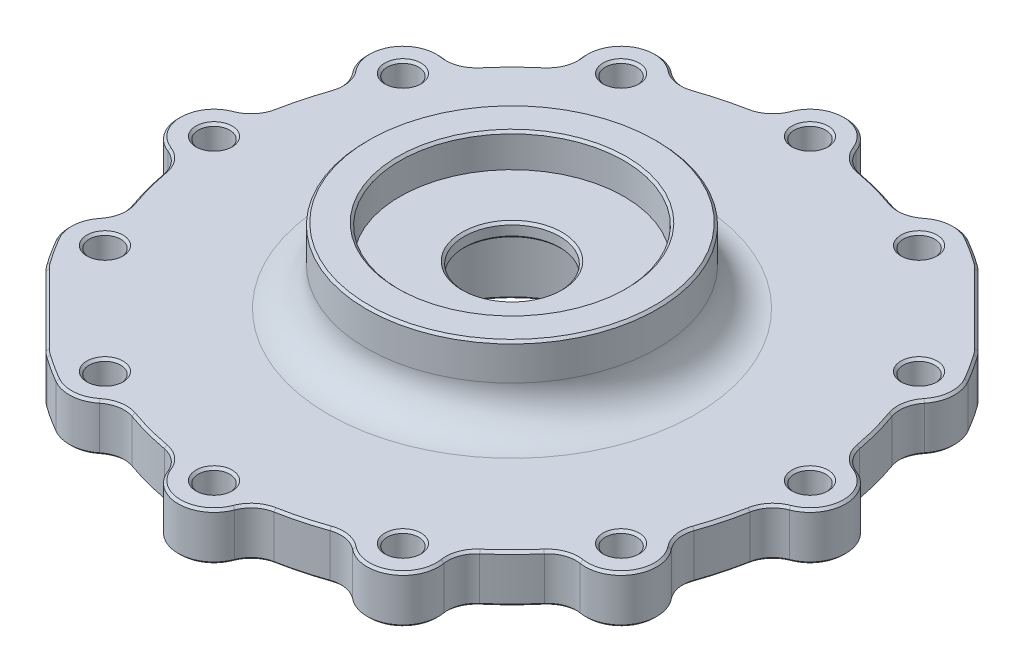
SolidWorks part; units mm, degrees
material "6061-T6 (SS)"
ref_plane "Front Plane" through (0, 0, 0) normal (0, 0, 1) x (1, 0, 0)
ref_plane "Top Plane" through (0, 0, 0) normal (0, 1, 0) x (1, 0, 0)
ref_plane "Right Plane" through (0, 0, 0) normal (1, 0, 0) x (0, 0, -1)
sketch "Sketch1" plane through (0, 0, 0) normal (0, 0, 1) x (1, 0, 0)
  line L1 (-70, -26.6983) -> (-45, -26.6983)
  line L18 (-45, -26.6983) -> (-45, -31.6983)
  line L23 (0, 95.7864) -> (0, -110.3116) construction
  line L28 (-70, -26.6983) -> (-70, -16.6983)
  line L29 (-70, -16.6983) -> (-38.5, -16.6983)
  line L30 (-30.5, -8.6983) -> (-30.5, -1.0983)
  line L31 (-30.5, -1.0983) -> (-23.5, -1.0983)
  line L32 (-23.5, -1.0983) -> (-23.5, -8.0983)
  line L40 (-23.5, -11.0983) -> (-10, -11.0983)
  line L41 (-10, -11.0983) -> (-10, -8.0983)
  line L42 (-10, -8.0983) -> (-23.5, -8.0983)
  line L43 (-23.5, -11.0983) -> (-23.5, -31.6983)
  line L44 (-45, -31.6983) -> (-23.5, -31.6983)
  line L45 (-38.5, -16.6983) -> (-70, -16.6983)
  arc A1 (-30.5, -8.6983) -> (-38.5, -16.6983) centre (-38.5, -8.6983) cw
  point P31 (-70, -16.6983)
  dimension "D1" = 45
  dimension "D10" = 20
  dimension "D2" = 8
  dimension "D7" = 7
  dimension "D3" = 7
  dimension "D4" = 10
  dimension "D5" = 5
  dimension "D6" = 20.6
  dimension "D8" = 47
  dimension "D11" = 3
revolve "Revolve1" add sketch "Sketch1" angle 360 about L23
sketch "Sketch2" plane through (0, -16.6983, 0) normal (0, 1, 0) x (1, 0, 0)
  circle A0 centre (0, 0) radius 62.5 construction
  point P0 (0, 0)
  point P3 (31.25, -54.1266)
  point P7 (0, -62.5)
  point P8 (-31.25, -54.1266)
  point P9 (-54.1266, -31.25)
  point P10 (-62.5, 0)
  point P11 (-54.1266, 31.25)
  point P12 (-31.25, 54.1266)
  point P13 (0, 62.5)
  point P14 (31.25, 54.1266)
  point P15 (54.1266, 31.25)
  point P16 (62.5, 0)
  point P17 (54.1266, -31.25)
  point P18 (0, 0)
  dimension "D1" = 125
  dimension "D2" = 12
sketch "Sketch4" plane through (0, -16.6983, 0) normal (0, 1, 0) x (1, 0, 0)
  circle A0 centre (0, 0) radius 62.5 construction
  point P3 (0, 62.5)
  point P7 (31.25, 54.1266)
  point P8 (54.1266, 31.25)
  point P9 (62.5, 0)
  point P10 (54.1266, -31.25)
  point P11 (31.25, -54.1266)
  point P12 (0, -62.5)
  point P13 (-31.25, -54.1266)
  point P14 (-54.1266, -31.25)
  point P15 (-62.5, 0)
  point P16 (-54.1266, 31.25)
  point P17 (-31.25, 54.1266)
  dimension "D1" = 125
hole_wizard "M6 Clearance Hole1" positions "Sketch4" profile "Sketch5" hole size "M6" standard "ANSI Metric" end condition through all
sketch "Sketch5" plane through (-31.25, -16.6983, -54.1266) normal (1, 0, 0) x (0, 0, 1)
  line L0 (0, 0) -> (0, 15)
  line L1 (0, 15) -> (3.3, 15)
  line L2 (3.3, 15) -> (3.3, 0)
  line L5 (3.3, 0) -> (0, 0)
  line L11 (0, -6.35) -> (0, 107.95) construction
  dimension "Thru Hole Dia." = 6.6
  dimension "Thru Hole Depth" = 15
hole_wizard "M6 Clearance Hole2" positions "Sketch2" profile "Sketch3" hole size "M6" standard "ANSI Metric" end condition through all
sketch "Sketch3" plane through (0, -16.6983, 0) normal (1, 0, 0) x (0, 0, 1)
  line L0 (0, 0) -> (0, 15)
  line L1 (0, 15) -> (3.3, 15)
  line L2 (3.3, 15) -> (3.3, 0)
  line L5 (3.3, 0) -> (0, 0)
  line L11 (0, -6.35) -> (0, 107.95) construction
  dimension "Thru Hole Dia." = 6.6
  dimension "Thru Hole Depth" = 15
sketch "Sketch6" plane through (0, -16.6983, 0) normal (0, 1, 0) x (1, 0, 0)
  line L0 (56.1324, 41.6107) -> (41.6107, 56.1324)
  line L1 (-56.1324, -41.6107) -> (-41.6107, -56.1324)
  arc A44 (26.5264, -59.9522) -> (20.7551, -58.9532) centre (22.7475, -64.6127) ccw
  arc A46 (26.5264, -59.9522) -> (38.6569, -52.9486) centre (31.25, -54.1266) ccw
  arc A47 (40.6774, -47.451) -> (38.6569, -52.9486) centre (44.5825, -52.0063) ccw
  arc A48 (40.6774, -47.451) -> (47.451, -40.6774) centre (0, 0) ccw
  arc A49 (52.9486, -38.6569) -> (47.451, -40.6774) centre (52.0063, -44.5825) ccw
  arc A50 (52.9486, -38.6569) -> (59.9522, -26.5264) centre (54.1266, -31.25) ccw
  arc A51 (58.9532, -20.7551) -> (59.9522, -26.5264) centre (64.6127, -22.7475) ccw
  arc A52 (58.9532, -20.7551) -> (61.4325, -11.5022) centre (0, 0) ccw
  arc A53 (65.1833, -7.0036) -> (61.4325, -11.5022) centre (67.33, -12.6064) ccw
  arc A54 (65.1833, -7.0036) -> (65.1833, 7.0036) centre (62.5, 0) ccw
  arc A55 (61.4325, 11.5022) -> (65.1833, 7.0036) centre (67.33, 12.6064) ccw
  arc A56 (61.4325, 11.5022) -> (58.9532, 20.7551) centre (0, 0) ccw
  arc A57 (59.9522, 26.5264) -> (58.9532, 20.7551) centre (64.6127, 22.7475) ccw
  arc A58 (59.9522, 26.5264) -> (60.6218, 35) centre (54.1266, 31.25) ccw
  arc A59 (60.6218, 35) -> (57.2382, 40.2963) centre (0, 0) ccw
  arc A60 (57.2382, 40.2963) -> (56.1324, 41.6107) centre (49.0613, 34.5396) ccw
  arc A61 (41.6107, 56.1324) -> (40.2963, 57.2382) centre (34.5396, 49.0613) ccw
  arc A62 (40.2963, 57.2382) -> (35, 60.6218) centre (0, 0) ccw
  arc A63 (35, 60.6218) -> (26.5264, 59.9522) centre (31.25, 54.1266) ccw
  arc A64 (20.7551, 58.9532) -> (26.5264, 59.9522) centre (22.7475, 64.6127) ccw
  arc A65 (20.7551, 58.9532) -> (11.5022, 61.4325) centre (0, 0) ccw
  arc A66 (7.0036, 65.1833) -> (11.5022, 61.4325) centre (12.6064, 67.33) ccw
  arc A67 (7.0036, 65.1833) -> (-7.0036, 65.1833) centre (0, 62.5) ccw
  arc A68 (-11.5022, 61.4325) -> (-7.0036, 65.1833) centre (-12.6064, 67.33) ccw
  arc A69 (-11.5022, 61.4325) -> (-20.7551, 58.9532) centre (0, 0) ccw
  arc A70 (-26.5264, 59.9522) -> (-20.7551, 58.9532) centre (-22.7475, 64.6127) ccw
  arc A71 (-26.5264, 59.9522) -> (-38.6569, 52.9486) centre (-31.25, 54.1266) ccw
  arc A72 (-40.6774, 47.451) -> (-38.6569, 52.9486) centre (-44.5825, 52.0063) ccw
  arc A73 (-40.6774, 47.451) -> (-47.451, 40.6774) centre (0, 0) ccw
  arc A74 (-52.9486, 38.6569) -> (-47.451, 40.6774) centre (-52.0063, 44.5825) ccw
  arc A75 (-52.9486, 38.6569) -> (-59.9522, 26.5264) centre (-54.1266, 31.25) ccw
  arc A76 (-58.9532, 20.7551) -> (-59.9522, 26.5264) centre (-64.6127, 22.7475) ccw
  arc A77 (-58.9532, 20.7551) -> (-61.4325, 11.5022) centre (0, 0) ccw
  arc A78 (-65.1833, 7.0036) -> (-61.4325, 11.5022) centre (-67.33, 12.6064) ccw
  arc A79 (-65.1833, 7.0036) -> (-65.1833, -7.0036) centre (-62.5, 0) ccw
  arc A80 (-61.4325, -11.5022) -> (-65.1833, -7.0036) centre (-67.33, -12.6064) ccw
  arc A81 (-61.4325, -11.5022) -> (-58.9532, -20.7551) centre (0, 0) ccw
  arc A82 (-59.9522, -26.5264) -> (-58.9532, -20.7551) centre (-64.6127, -22.7475) ccw
  arc A83 (-59.9522, -26.5264) -> (-60.6218, -35) centre (-54.1266, -31.25) ccw
  arc A84 (-60.6218, -35) -> (-57.2382, -40.2963) centre (0, 0) ccw
  arc A85 (-57.2382, -40.2963) -> (-56.1324, -41.6107) centre (-49.0613, -34.5396) ccw
  arc A86 (-41.6107, -56.1324) -> (-40.2963, -57.2382) centre (-34.5396, -49.0613) ccw
  arc A87 (-40.2963, -57.2382) -> (-35, -60.6218) centre (0, 0) ccw
  arc A88 (-35, -60.6218) -> (-26.5264, -59.9522) centre (-31.25, -54.1266) ccw
  arc A89 (-20.7551, -58.9532) -> (-26.5264, -59.9522) centre (-22.7475, -64.6127) ccw
  arc A90 (-20.7551, -58.9532) -> (-11.5022, -61.4325) centre (0, 0) ccw
  arc A91 (-7.0036, -65.1833) -> (-11.5022, -61.4325) centre (-12.6064, -67.33) ccw
  arc A92 (-7.0036, -65.1833) -> (7.0036, -65.1833) centre (0, -62.5) ccw
  arc A93 (11.5022, -61.4325) -> (7.0036, -65.1833) centre (12.6064, -67.33) ccw
  arc A94 (11.5022, -61.4325) -> (20.7551, -58.9532) centre (0, 0) ccw
  circle M71 centre (0, 0) radius 70
extrude "Cut-Extrude1" cut sketch "Sketch6" against normal through all contours A71 A70 A69 A68 A67 M71 | A67 A66 A65 A64 A63 M71 | A75 A74 A73 A72 A71 M71 | A79 A78 A77 A76 A75 M71 | A83 A82 A81 A80 A79 M71 | A92 A91 A90 A89 A88 M71 | A94 A93 A92 A46 A44 M71 | A50 A49 A48 A47 A46 M71 | A54 A53 A52 A51 A50 M71 | A58 A57 A56 A55 A54 M71 | A86 L1 A85 M71 | A61 L0 A60 M71
chamfer "Chamfer1" distance 0.5 angle 45 135 edges at (54.1266, -26.6983, -34.55) (54.1266, -16.6983, -27.95) (31.25, -26.6983, -57.4266) (31.25, -16.6983, -50.8266) (0, -26.6983, -65.8) (0, -16.6983, -59.2) (0, -1.0983, 30.5) (0, -1.0983, 23.5) (0, -8.0983, 10) (0, -11.0983, 10) (0, -31.6983, 23.5) (0, -31.6983, 45) (0, -26.6983, 45) (62.7217, -26.6983, 8.7641) (60.3704, -26.6983, 16.1762) (58.7006, -26.6983, 23.7709) (60.6218, -26.6983, 35) (70, -26.6983, 0) (8.7641, -26.6983, 62.7217) (0, -26.6983, 70) (16.1762, -26.6983, 60.3704) (23.7709, -26.6983, 58.7006) (35, -26.6983, 60.6218) (-62.7217, -26.6983, -8.7641) (-60.3704, -26.6983, -16.1762) (-58.7006, -26.6983, -23.7709) (-60.6218, -26.6983, -35) (-70, -26.6983, 0) (-23.7709, -26.6983, -58.7006) (-16.1762, -26.6983, -60.3704) (-8.7641, -26.6983, -62.7217) (0, -26.6983, -70) (-35, -26.6983, -60.6218) (-35, -16.6983, -60.6218) (0, -16.6983, -70) (-16.1762, -16.6983, -60.3704) (-23.7709, -16.6983, -58.7006) (-8.7641, -16.6983, -62.7217) (-70, -16.6983, 0) (-60.6218, -16.6983, -35) (-60.3704, -16.6983, -16.1762) (-62.7217, -16.6983, -8.7641) (-58.7006, -16.6983, -23.7709) (16.1762, -16.6983, 60.3704) (35, -16.6983, 60.6218) (0, -16.6983, 70) (8.7641, -16.6983, 62.7217) (23.7709, -16.6983, 58.7006) (70, -16.6983, 0) (60.6218, -16.6983, 35) (60.3704, -16.6983, 16.1762) (62.7217, -16.6983, 8.7641) (58.7006, -16.6983, 23.7709) (-49.9365, -26.6983, -38.9508) (-44.1942, -26.6983, -44.1942) (-38.9508, -26.6983, -49.9365) (8.7641, -26.6983, -62.7217) (16.1762, -26.6983, -60.3704) (23.7709, -26.6983, -58.7006) (30.6592, -26.6983, -61.6033) (30.6592, -16.6983, -61.6033) (16.1762, -16.6983, -60.3704) (8.7641, -16.6983, -62.7217) (23.7709, -16.6983, -58.7006) (-44.1942, -16.6983, -44.1942) (-49.9365, -16.6983, -38.9508) (-38.9508, -16.6983, -49.9365) (-58.9895, -26.6983, 37.6861) (-58.9895, -16.6983, 37.6861) (-8.7641, -26.6983, 62.7217) (-16.1762, -26.6983, 60.3704) (-23.7709, -26.6983, 58.7006) (-58.7006, -26.6983, 23.7709) (-60.3704, -26.6983, 16.1762) (-62.7217, -26.6983, 8.7641) (-61.6033, -26.6983, 30.6592) (-61.6033, -16.6983, 30.6592) (-60.3704, -16.6983, 16.1762) (-58.7006, -16.6983, 23.7709) (-62.7217, -16.6983, 8.7641) (-30.6592, -26.6983, 61.6033) (-30.6592, -16.6983, 61.6033) (-16.1762, -16.6983, 60.3704) (-8.7641, -16.6983, 62.7217) (-23.7709, -16.6983, 58.7006) (49.9365, -26.6983, 38.9508) (44.1942, -26.6983, 44.1942) (38.9508, -26.6983, 49.9365) (44.1942, -16.6983, 44.1942) (49.9365, -16.6983, 38.9508) (38.9508, -16.6983, 49.9365) (58.9895, -26.6983, -37.6861) (37.6861, -26.6983, -58.9895) (58.9895, -16.6983, -37.6861) (37.6861, -16.6983, -58.9895) (-37.6861, -26.6983, 58.9895) (-37.6861, -16.6983, 58.9895) (48.8715, -26.6983, -48.8715) (-48.8715, -26.6983, 48.8715) (58.7006, -26.6983, -23.7709) (60.3704, -26.6983, -16.1762) (62.7217, -26.6983, -8.7641) (61.6033, -26.6983, -30.6592) (61.6033, -16.6983, -30.6592) (60.3704, -16.6983, -16.1762) (58.7006, -16.6983, -23.7709) (62.7217, -16.6983, -8.7641) (-40.9773, -26.6983, 56.7136) (-40.9773, -16.6983, 56.7136) (-56.7136, -26.6983, 40.9773) (-56.7136, -16.6983, 40.9773) (-48.8715, -16.6983, 48.8715) (-31.25, -26.6983, -57.4266) (-31.25, -16.6983, -50.8266) (40.9773, -26.6983, -56.7136) (40.9773, -16.6983, -56.7136) (56.7136, -26.6983, -40.9773) (56.7136, -16.6983, -40.9773) (48.8715, -16.6983, -48.8715) (-54.1266, -26.6983, -34.55) (-54.1266, -16.6983, -27.95) (-62.5, -26.6983, -3.3) (-62.5, -16.6983, 3.3) (-54.1266, -26.6983, 27.95) (-54.1266, -16.6983, 34.55) (-31.25, -26.6983, 50.8266) (-31.25, -16.6983, 57.4266) (0, -26.6983, 59.2) (0, -16.6983, 65.8) (31.25, -26.6983, 50.8266) (31.25, -16.6983, 57.4266) (54.1266, -26.6983, 27.95) (54.1266, -16.6983, 34.55) (62.5, -26.6983, -3.3) (62.5, -16.6983, 3.3)
fillet "Fillet1" [suppressed] radius 0.381
